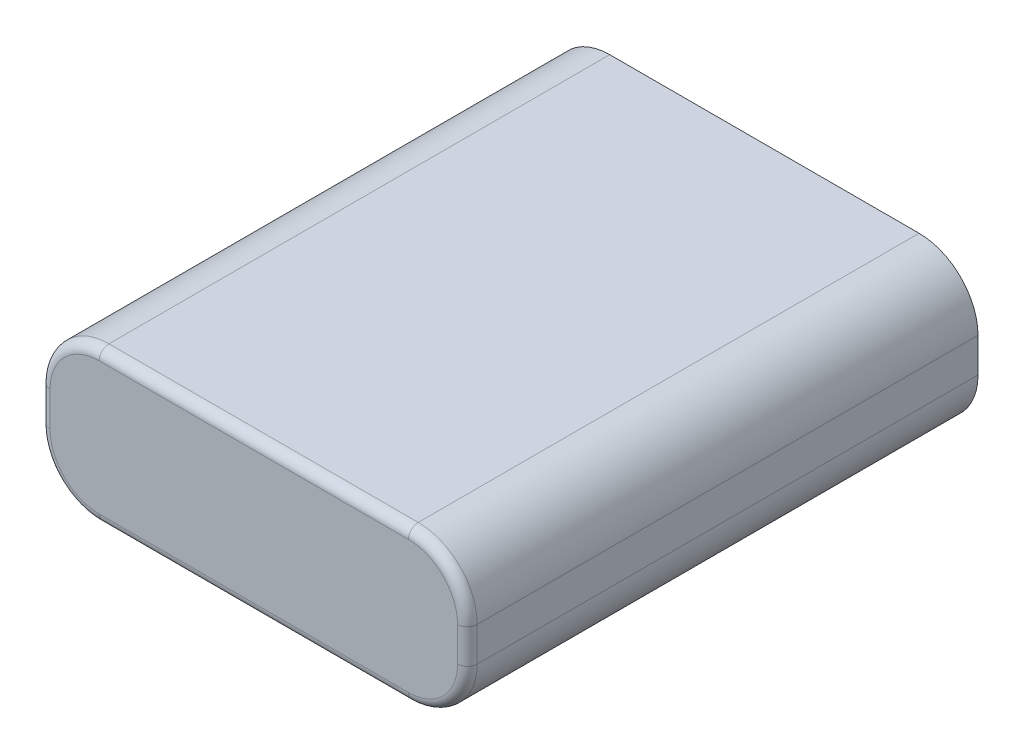
SolidWorks part; units mm, degrees
ref_plane "Front Plane" through (0, 0, 0) normal (0, 0, 1) x (1, 0, 0)
ref_plane "Top Plane" through (0, 0, 0) normal (0, 1, 0) x (1, 0, 0)
ref_plane "Right Plane" through (0, 0, 0) normal (1, 0, 0) x (0, 0, -1)
sketch "Sketch2" plane through (0, 0, 0) normal (0, 0, 1) x (1, 0, 0)
  line L1 (-15.75, -7.75) -> (15.75, -7.75)
  line L2 (-21.75, -1.75) -> (-21.75, 1.75)
  line L3 (-15.75, 7.75) -> (15.75, 7.75)
  line L4 (21.75, -1.75) -> (21.75, 1.75)
  line L5 (-21.75, -7.75) -> (21.75, 7.75) construction
  line L6 (-21.75, 7.75) -> (21.75, -7.75) construction
  arc A0 (15.75, 7.75) -> (21.75, 1.75) centre (15.75, 1.75) cw
  arc A1 (15.75, -7.75) -> (21.75, -1.75) centre (15.75, -1.75) ccw
  arc A2 (-15.75, -7.75) -> (-21.75, -1.75) centre (-15.75, -1.75) cw
  arc A3 (-21.75, 1.75) -> (-15.75, 7.75) centre (-15.75, 1.75) cw
  point P0 (0, 0)
  dimension "D3" = 6
  dimension "D1" = 15.5
  dimension "D2" = 43.5
extrude "Boss-Extrude1" add sketch "Sketch2" along normal blind 52
fillet "Fillet1" radius 1 8 edges at (19.9926, 5.9926, 52) (21.75, 0, 52) (19.9926, -5.9926, 52) (0, -7.75, 52) (-19.9926, -5.9926, 52) (-21.75, 0, 52) (-19.9926, 5.9926, 52) (0, 7.75, 52)
